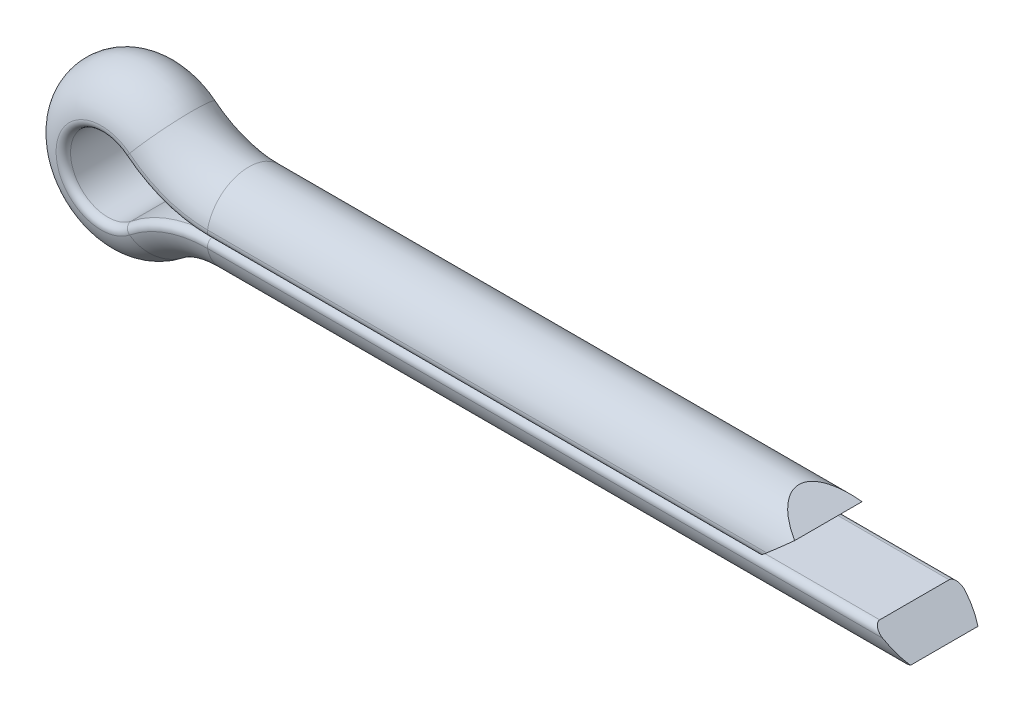
SolidWorks part; units mm, degrees
ref_plane "Front Plane" through (0, 0, 0) normal (0, 0, 1) x (1, 0, 0)
ref_plane "Top Plane" through (0, 0, 0) normal (0, 1, 0) x (1, 0, 0)
ref_plane "Right Plane" through (0, 0, 0) normal (1, 0, 0) x (0, 0, -1)
other "Configuration Table"
sketch "PathSke" plane through (0, 0, 0) normal (0, 0, 1) x (1, 0, 0)
  line L0 (0, 0) -> (38.8652, 0) construction
  line L1 (0, 0) -> (0, 12.2501) construction
  line L2 (3.665, 0) -> (3.665, 12.2501) construction
  line L3 (3.665, 1.45) -> (23.665, 1.45)
  line L4 (3.665, -1.45) -> (27.665, -1.45)
  line L5 (0, 0) -> (-2.735, 0) construction
  arc A0 (1.7079, 2.1362) -> (1.7079, -2.1362) centre (0, 0) ccw
  arc A1 (3.665, 1.45) -> (1.7079, 2.1362) centre (3.665, 4.584) cw
  arc A2 (3.665, -1.45) -> (1.7079, -2.1362) centre (3.665, -4.584) ccw
ref_plane "SectionPlane" through (23.665, 1.45, 0) normal (1, 0, 0) x (0, 0, -1)
sketch "SectionSke" plane through (23.665, 1.45, 0) normal (1, 0, 0) x (0, 0, -1)
  line L0 (0, -1.45) -> (0, 8.6928) construction
  line L1 (0, -1.45) -> (0, 10.8001) construction
  line L2 (-1.45, -1.45) -> (1.45, -1.45) construction
  line L3 (-1.1977, -1.448) -> (1.1977, -1.448)
  arc A0 (1.4235, -1.1743) -> (-1.4235, -1.1743) centre (0, -1.45) ccw
  arc A1 (-1.1977, -1.448) -> (-1.4235, -1.1743) centre (-1.1977, -1.218) cw
  arc A2 (1.4235, -1.1743) -> (1.1977, -1.448) centre (1.1977, -1.218) cw
  dimension "D1" = 0.002
sweep "BaseBody" add profiles "SectionSke" path "PathSke"
sketch "ConeCutSke" plane through (0, 0, 0) normal (0, 0, 1) x (1, 0, 0)
  line L0 (0, 0) -> (34.6884, 0) construction
  line L1 (22.6339, 1.46) -> (27.675, 1.46)
  line L2 (27.675, 1.46) -> (27.675, -1.46)
  line L3 (23.665, 1.45) -> (3.665, 1.45) construction
  line L4 (22.6339, 1.46) -> (23.665, 0.8629)
  line L5 (23.665, 0.2757) -> (23.665, 1.45) construction
  line L6 (23.665, 0.8629) -> (22.6339, 0)
  line L7 (22.6339, 0) -> (26.6339, 0)
  line L8 (26.6339, 0) -> (27.665, -0.8629)
  line L9 (27.665, -1.45) -> (27.665, -0.2757) construction
  line L10 (27.665, -0.8629) -> (26.6339, -1.46)
  line L11 (26.6339, -1.46) -> (27.675, -1.46)
  point P19 (27.675, 0)
  dimension "D1" = 0.01
  dimension "D2" = 70
  dimension "D3" = 70
  dimension "D4" = 0.01
extrude "ConeCut" cut sketch "ConeCutSke" against normal through all and the other way through all
equation "\"Diameter@SectionSke\" = \"Diameter@PathSke\""
